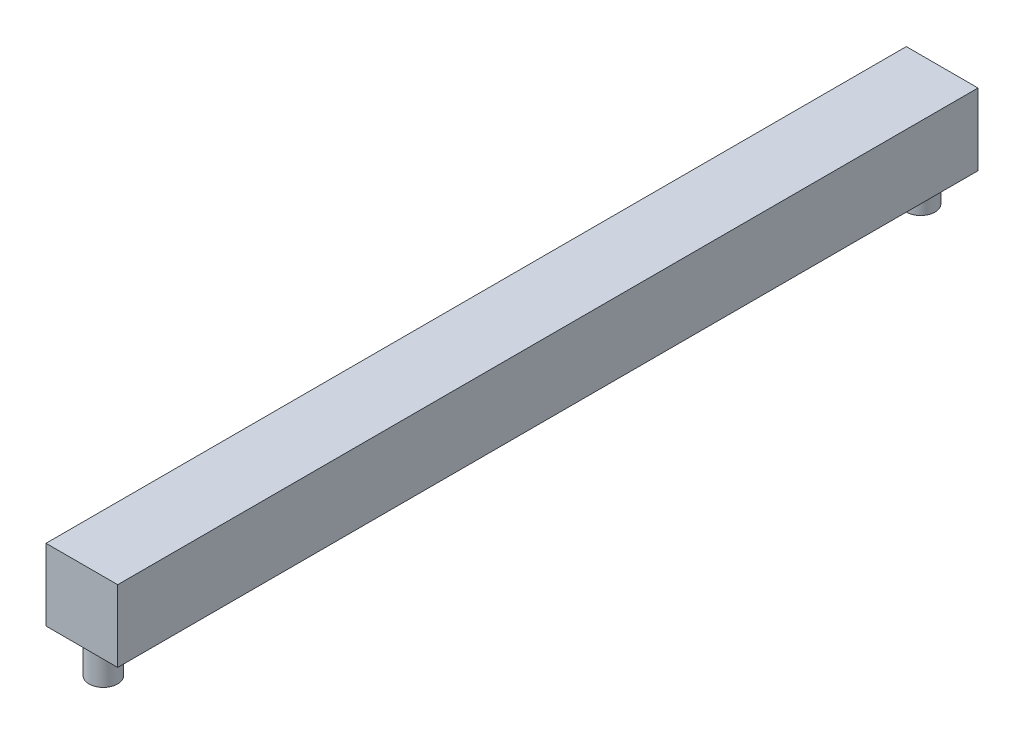
SolidWorks part; units mm, degrees
ref_plane "Front Plane" through (0, 0, 0) normal (0, 0, 1) x (1, 0, 0)
ref_plane "Top Plane" through (0, 0, 0) normal (0, 1, 0) x (1, 0, 0)
ref_plane "Right Plane" through (0, 0, 0) normal (1, 0, 0) x (0, 0, -1)
sketch "Sketch1" plane through (0, 0, 0) normal (0, 1, 0) x (1, 0, 0)
  line L1 (-3.3944, 52.3601) -> (6.6056, 52.3601)
  line L2 (-3.3944, 52.3601) -> (-3.3944, -67.6399)
  line L3 (-3.3944, -67.6399) -> (6.6056, -67.6399)
  line L4 (6.6056, 52.3601) -> (6.6056, -67.6399)
  dimension "D1" = 120
  dimension "D2" = 10
extrude "Boss-Extrude1" add sketch "Sketch1" along normal blind 10
sketch "Sketch2" plane through (0, 0, 0) normal (0, -1, 0) x (-1, 0, 0)
  line L0 (-6.6056, 52.3601) -> (3.3944, 52.3601) construction
  line L1 (3.3944, -67.6399) -> (-6.6056, -67.6399) construction
  circle A0 centre (-1.6056, 49.3601) radius 2
  circle A1 centre (-1.6056, -64.6399) radius 2
  dimension "D1" = 3
  dimension "D2" = 3
extrude "Boss-Extrude2" add sketch "Sketch2" along normal blind 5
